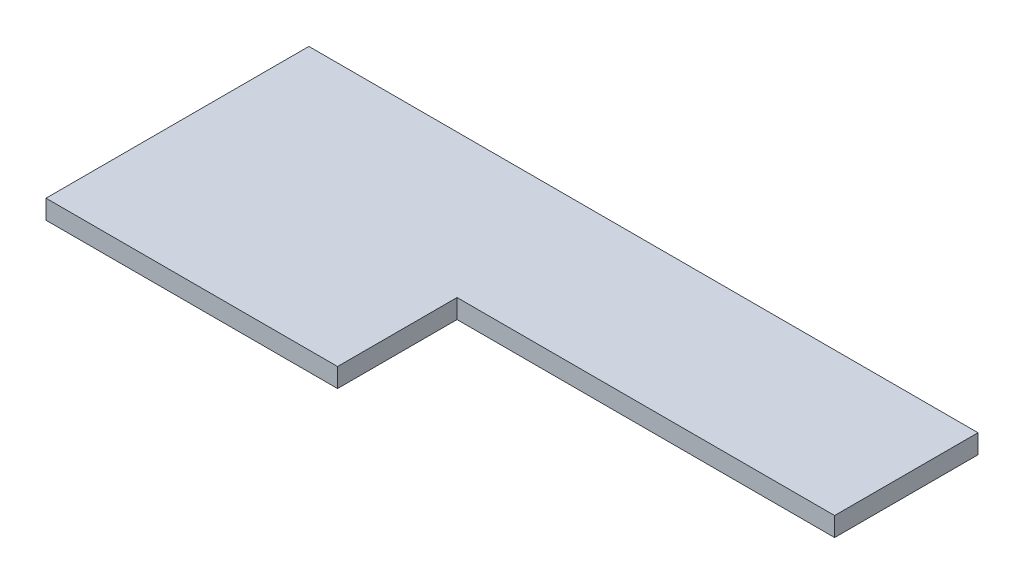
SolidWorks part; units mm, degrees
ref_plane "Front Plane" through (0, 0, 0) normal (0, 0, 1) x (1, 0, 0)
ref_plane "Top Plane" through (0, 0, 0) normal (0, 1, 0) x (1, 0, 0)
ref_plane "Right Plane" through (0, 0, 0) normal (1, 0, 0) x (0, 0, -1)
sketch "Sketch2" plane through (0, 0, 0) normal (0, 1, 0) x (1, 0, 0)
  line L0 (-55.9197, 21.2751) -> (84.0803, 21.2751)
  line L1 (84.0803, 21.2751) -> (84.0803, -8.7249)
  line L2 (84.0803, -8.7249) -> (5.0803, -8.7249)
  line L3 (5.0803, -8.7249) -> (5.0803, -33.7249)
  line L4 (5.0803, -33.7249) -> (-55.9197, -33.7249)
  line L5 (-55.9197, -33.7249) -> (-55.9197, 21.2751)
  dimension "D2" = 61
  dimension "D3" = 25
  dimension "D4" = 79
  dimension "D5" = 30
extrude "Boss-Extrude1" add sketch "Sketch2" along normal blind 4
